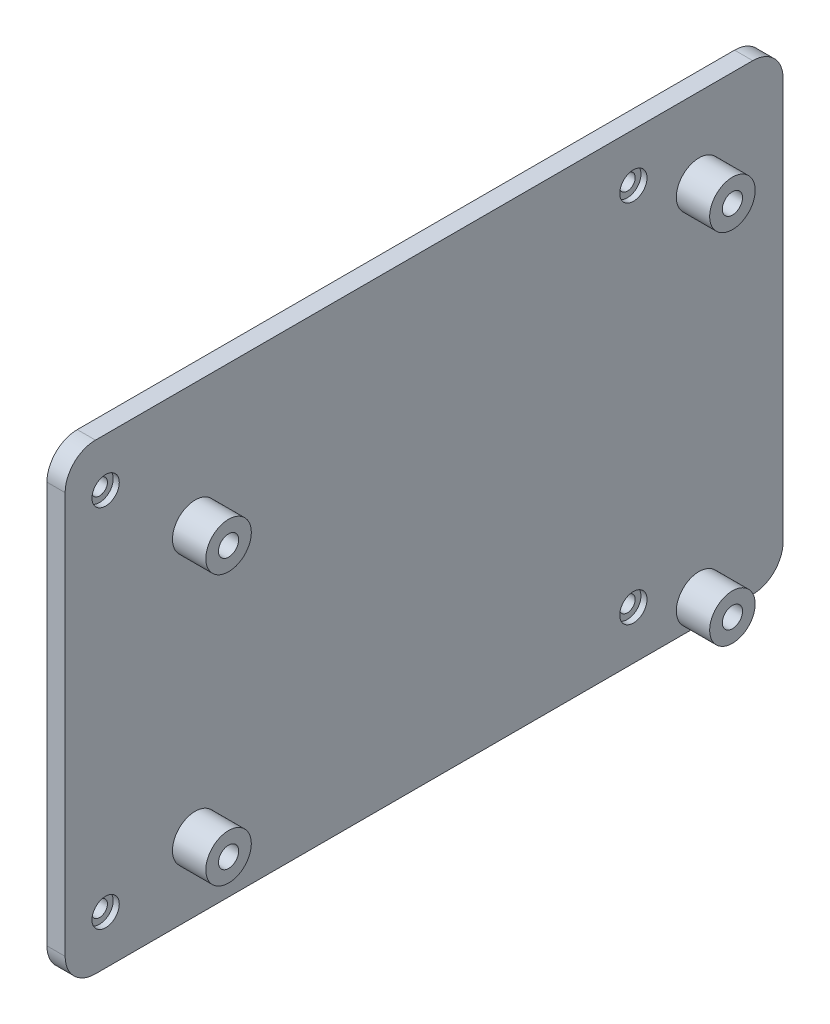
SolidWorks part; units mm, degrees
material "ABS"
ref_plane "X-Y Datum" through (0, 0, 0) normal (0, 0, 1) x (1, 0, 0)
ref_plane "X-Z Datum" through (0, 0, 0) normal (0, 1, 0) x (1, 0, 0)
ref_plane "Y-Z Datum" through (0, 0, 0) normal (1, 0, 0) x (0, 0, -1)
sketch "Sketch1" plane through (0, 0, 0) normal (1, 0, 0) x (0, 0, -1)
  line L1 (-66.675, 38.1) -> (66.675, 38.1)
  line L2 (-66.675, 38.1) -> (-66.675, -38.1)
  line L3 (-66.675, -38.1) -> (66.675, -38.1)
  line L4 (66.675, 38.1) -> (66.675, -38.1)
  line L5 (-66.675, 38.1) -> (66.675, -38.1) construction
  line L6 (-66.675, -38.1) -> (66.675, 38.1) construction
  point P0 (0, 0)
  dimension "D1" = 133.35
  dimension "D2" = 76.2
extrude "Boss-Extrude1" add sketch "Sketch1" along normal blind 3
sketch "Sketch4" plane through (3, 0, 0) normal (1, 0, 0) x (0, 0, -1)
  circle A1 centre (-45, -30.1) radius 3.75
  circle A2 centre (-45, -30.1) radius 3.75
  circle A3 centre (-45, 30.1) radius 3.75
  circle A4 centre (-45, 30.1) radius 3.75
  circle A5 centre (42, 30.1) radius 3.75
  circle A6 centre (42, 30.1) radius 3.75
  circle A7 centre (42, -30.1) radius 3.75
  circle A8 centre (42, -30.1) radius 3.75
  circle A9 centre (-45, 30.1) radius 1.665
  circle A10 centre (-45, 30.1) radius 1.665
  circle A11 centre (-45, -30.1) radius 1.665
  circle A12 centre (-45, -30.1) radius 1.665
  circle A13 centre (42, -30.1) radius 1.665
  circle A14 centre (42, -30.1) radius 1.665
  circle A15 centre (42, 30.1) radius 1.665
  circle A16 centre (42, 30.1) radius 1.665
  dimension "D1" = 0
  dimension "D2" = 0
  dimension "D3" = 0
  dimension "D4" = 0
  dimension "D5" = 0
  dimension "D6" = 0
  dimension "D7" = 0
  dimension "D8" = 0
hole_wizard "M2 Clearance Hole1" positions "Sketch5" profile "Sketch6" hole size "M2" standard "ANSI Metric" end condition through all
sketch "Sketch5" plane through (3, 0, 0) normal (1, 0, 0) x (0, 0, -1)
  point P0 (-45, -30.1)
  point P3 (-45, 30.1)
  point P6 (42, 30.1)
  point P9 (42, -30.1)
sketch "Sketch6" plane through (3, -30.1, 45) normal (0, 1, 0) x (0, 0, -1)
  line L0 (0, 0) -> (0, 3)
  line L1 (0, 3) -> (1.3, 3)
  line L2 (1.3, 3) -> (1.3, 0)
  line L5 (1.3, 0) -> (0, 0)
  line L11 (0, -6.35) -> (0, 107.95) construction
  dimension "Thru Hole Dia." = 2.6
  dimension "Thru Hole Depth" = 3
sketch "Sketch7" plane through (3, 0, 0) normal (1, 0, 0) x (0, 0, -1)
  circle A1 centre (-30.2315, 17.584) radius 1.7 construction
  circle A3 centre (-30.2315, 17.584) radius 1.665
  circle A5 centre (52.8265, 24.895) radius 1.7 construction
  circle A7 centre (52.8265, -34.163) radius 1.7 construction
  circle A80 centre (-30.2315, -26.855) radius 1.7 construction
  circle A81 centre (-30.2315, 17.584) radius 1.7 construction
  circle A82 centre (52.8265, 24.895) radius 1.7 construction
  circle A83 centre (52.8265, -34.163) radius 1.7 construction
  circle A84 centre (-30.2315, -26.855) radius 1.7 construction
  circle A85 centre (-30.2315, -26.855) radius 1.665
  circle A86 centre (-30.2315, -26.855) radius 3.75
  circle A87 centre (-30.2315, 17.584) radius 3.75
  circle A88 centre (52.8265, 24.895) radius 1.665
  circle A89 centre (52.8265, 24.895) radius 3.75
  circle A90 centre (52.8265, -34.163) radius 1.665
  circle A91 centre (52.8265, -34.163) radius 3.75
  line M17 (-66.675, -38.1) -> (66.675, -38.1)
  dimension "D1" = 3.33
  dimension "D3" = 7.5
extrude "Boss-Extrude2" add sketch "Sketch7" along normal blind 5.5 contours A91 A90 M17 | A89 A88 | A87 A3 | A86 A85
sketch "Sketch8" plane through (3, 0, 0) normal (1, 0, 0) x (0, 0, -1)
  line L0 (-51.675, -38.1) -> (-51.675, 38.1)
  line L2 (66.675, 38.1) -> (-66.675, 38.1) construction
  line L3 (-66.675, 38.1) -> (-66.675, -38.1) construction
  line L4 (-66.675, -38.1) -> (66.675, -38.1) construction
  dimension "D1" = 15
extrude "Cut-Extrude1" cut sketch "Sketch8" against normal through all
fillet "Fillet1" radius 5 4 edges at (1.5, -38.1, -66.675) (1.5, 38.1, -66.675) (1.5, 38.1, 51.675) (1.5, -38.1, 51.675)
sketch "Sketch9" plane through (3, 0, 0) normal (1, 0, 0) x (0, 0, -1)
  circle A0 centre (-45, -30.1) radius 2.25
  circle A1 centre (-45, 30.1) radius 2.25
  circle A2 centre (42, 30.1) radius 2.25
  circle A3 centre (42, -30.1) radius 2.25
  dimension "D1" = 4.5
extrude "Cut-Extrude2" cut sketch "Sketch9" against normal blind 1
